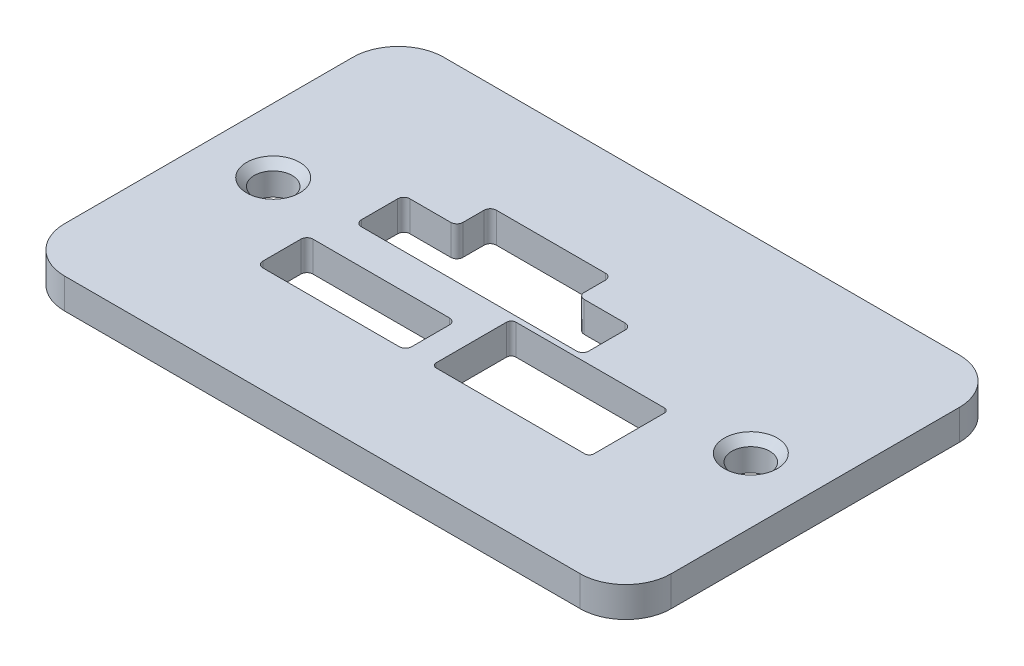
SolidWorks part; units mm, degrees
ref_plane "前视基准面" through (0, 0, 0) normal (0, 0, 1) x (1, 0, 0)
ref_plane "上视基准面" through (0, 0, 0) normal (0, 1, 0) x (1, 0, 0)
ref_plane "右视基准面" through (0, 0, 0) normal (1, 0, 0) x (0, 0, -1)
sketch "草图1" plane through (0, 0, 0) normal (0, 1, 0) x (1, 0, 0)
  line L1 (-17, 12.5) -> (17, 12.5)
  line L2 (-20, 9.5) -> (-20, -9.5)
  line L3 (-17, -12.5) -> (17, -12.5)
  line L4 (20, 9.5) -> (20, -9.5)
  line L5 (-20, 12.5) -> (20, -12.5) construction
  line L6 (-20, -12.5) -> (20, 12.5) construction
  arc A0 (-20, 9.5) -> (-17, 12.5) centre (-17, 9.5) cw
  arc A1 (20, 9.5) -> (17, 12.5) centre (17, 9.5) ccw
  arc A2 (20, -9.5) -> (17, -12.5) centre (17, -9.5) cw
  arc A3 (-17, -12.5) -> (-20, -9.5) centre (-17, -9.5) cw
  point P0 (0, 0)
  dimension "D3" = 3
  dimension "D4" = 3
  dimension "D1" = 40
  dimension "D2" = 25
extrude "凸台-拉伸1" add sketch "草图1" along normal blind 2
sketch "草图2" plane through (0, 2, 0) normal (0, 1, 0) x (1, 0, 0)
  line L0 (-22.5674, 0) -> (23.6783, 0) construction
  circle A0 centre (-15.75, 0) radius 1.25
  dimension "D2" = 2.5
  dimension "D1" = 15.75
extrude "切除-拉伸1" cut sketch "草图2" against normal up to next contours A0
chamfer "倒角1" distance 0.5 angle 45 1 edges at (-15.75, 2, 1.25)
mirror "镜向3" about plane through (0, 0, 0) normal (1, 0, 0) of "倒角1", "切除-拉伸1"
sketch "草图6" plane through (0, 2, 0) normal (0, 1, 0) x (1, 0, 0)
  line L0 (20, -9.5) -> (20, 9.5) construction
  line L1 (-10.036, 3.3) -> (-7.336, 3.3)
  line L2 (-10.436, 2.9) -> (-10.436, 0.5)
  line L3 (-10.036, 0.1) -> (4.164, 0.1)
  line L4 (4.564, 2.9) -> (4.564, 0.5)
  line L5 (-10.436, 3.3) -> (4.564, 0.1) construction
  line L6 (-10.436, 0.1) -> (4.564, 3.3) construction
  line L8 (17, 12.5) -> (-17, 12.5) construction
  line L9 (-10.925, -2.2) -> (-1.925, -2.2)
  line L10 (-11.325, -2.6) -> (-11.325, -5.1)
  line L11 (-10.925, -5.5) -> (-1.925, -5.5)
  line L12 (-1.525, -2.6) -> (-1.525, -5.1)
  line L13 (-11.325, -2.2) -> (-1.525, -5.5) construction
  line L14 (-11.325, -5.5) -> (-1.525, -2.2) construction
  line L15 (-17, -12.5) -> (17, -12.5) construction
  line L16 (-6.936, 3.7) -> (-6.936, 5.1)
  line L17 (0.5, -0.25) -> (10.3, -0.25)
  line L18 (0.2, -0.55) -> (0.2, -5.2)
  line L19 (0.5, -5.5) -> (10.3, -5.5)
  line L20 (10.6, -0.55) -> (10.6, -5.2)
  line L21 (0.2, -0.25) -> (10.6, -5.5) construction
  line L22 (0.2, -5.5) -> (10.6, -0.25) construction
  line L25 (-6.536, 5.5) -> (0.664, 5.5)
  line L27 (0.8804, 5.4364) -> (1.064, 5.5) construction
  line L28 (-6.936, 5.5) -> (-6.7481, 5.4392) construction
  line L29 (1.064, 3.7) -> (1.064, 5.1)
  line L30 (1.464, 3.3) -> (4.164, 3.3)
  arc A0 (-10.436, 2.9) -> (-10.036, 3.3) centre (-10.036, 2.9) cw
  arc A1 (4.164, 3.3) -> (4.564, 2.9) centre (4.164, 2.9) cw
  arc A2 (4.564, 0.5) -> (4.164, 0.1) centre (4.164, 0.5) cw
  arc A3 (-10.036, 0.1) -> (-10.436, 0.5) centre (-10.036, 0.5) cw
  arc A4 (-1.525, -5.1) -> (-1.925, -5.5) centre (-1.925, -5.1) cw
  arc A5 (-11.325, -2.6) -> (-10.925, -2.2) centre (-10.925, -2.6) cw
  arc A6 (-1.525, -2.6) -> (-1.925, -2.2) centre (-1.925, -2.6) ccw
  arc A7 (-10.925, -5.5) -> (-11.325, -5.1) centre (-10.925, -5.1) cw
  arc A8 (10.3, -0.25) -> (10.6, -0.55) centre (10.3, -0.55) cw
  arc A9 (10.3, -5.5) -> (10.6, -5.2) centre (10.3, -5.2) ccw
  arc A10 (0.5, -5.5) -> (0.2, -5.2) centre (0.5, -5.2) cw
  arc A11 (0.2, -0.55) -> (0.5, -0.25) centre (0.5, -0.55) cw
  arc A12 (-7.336, 3.3) -> (-6.936, 3.7) centre (-7.336, 3.7) ccw
  arc A13 (1.464, 3.3) -> (1.064, 3.7) centre (1.464, 3.7) cw
  arc A14 (1.064, 5.1) -> (0.664, 5.5) centre (0.664, 5.1) ccw
  arc A15 (-6.936, 5.1) -> (-6.536, 5.5) centre (-6.536, 5.1) cw
  point P0 (-2.936, 1.7)
  point P22 (-6.425, -3.85)
  point P41 (5.4, -2.875)
  point P57 (-2.8017, 4.1613)
  point P67 (-6.936, 3.3)
  point P70 (1.064, 3.3)
  dimension "D5" = 0.4
  dimension "D6" = 0.4
  dimension "D8" = 0.4
  dimension "D9" = 0.4
  dimension "D15" = 0.3
  dimension "D19" = 0.4
  dimension "D1" = 22.936
  dimension "D2" = 15
  dimension "D3" = 3.2
  dimension "D4" = 7
  dimension "D7" = 3.3
  dimension "D10" = 9.8
  dimension "D11" = 7
  dimension "D12" = 26.425
  dimension "D13" = 5.25
  dimension "D14" = 10.4
  dimension "D16" = 14.6
  dimension "D17" = 8
  dimension "D18" = 2.2
  dimension "D20" = 3.5
extrude "切除-拉伸5" cut sketch "草图6" against normal up to next
